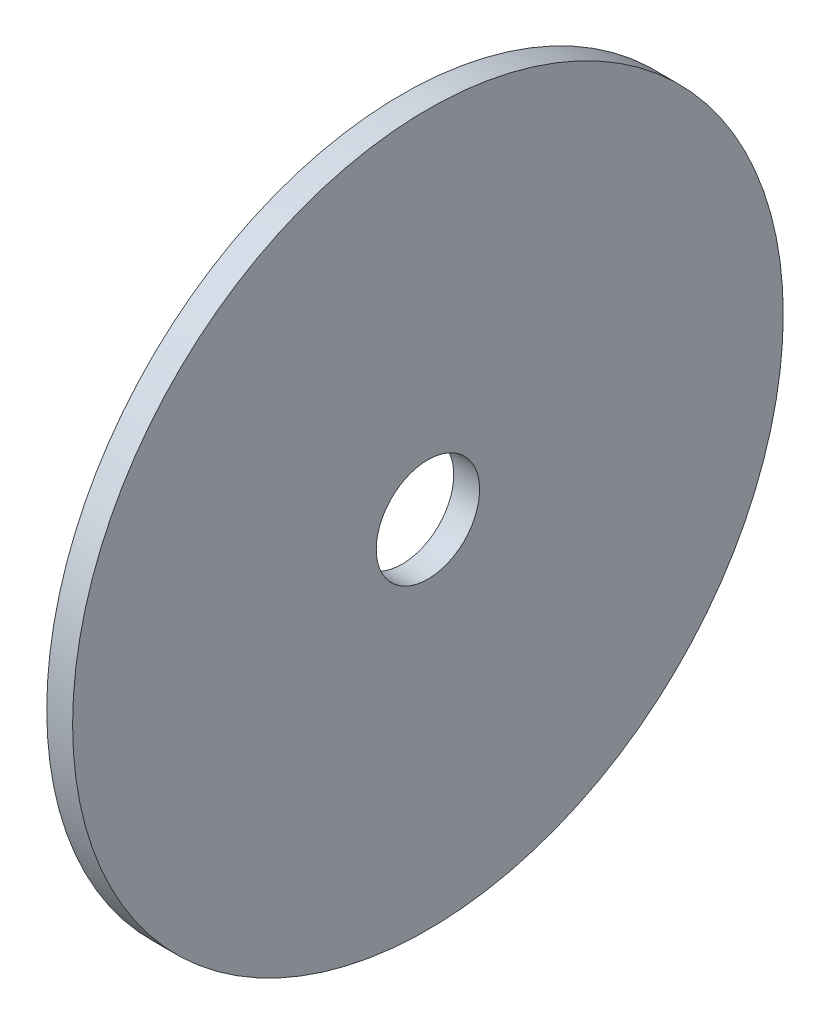
SolidWorks part; units mm, degrees
ref_plane "Front Plane" through (0, 0, 0) normal (0, 0, 1) x (1, 0, 0)
ref_plane "Top Plane" through (0, 0, 0) normal (0, 1, 0) x (1, 0, 0)
ref_plane "Right Plane" through (0, 0, 0) normal (1, 0, 0) x (0, 0, -1)
sketch "Axial profile (mm)" plane through (0, 0, 0) normal (0, 0, 1) x (1, 0, 0)
  line L0 (-110, 0) -> (75, 0) construction
  line L1 (-130, 8) -> (-126, 8)
  line L2 (-126, 8) -> (-126, 55)
  line L3 (-126, 55) -> (-130, 55)
  line L4 (-130, 55) -> (-130, 8)
revolve "Full revolution" add sketch "Axial profile (mm)" angle 360 about L0
